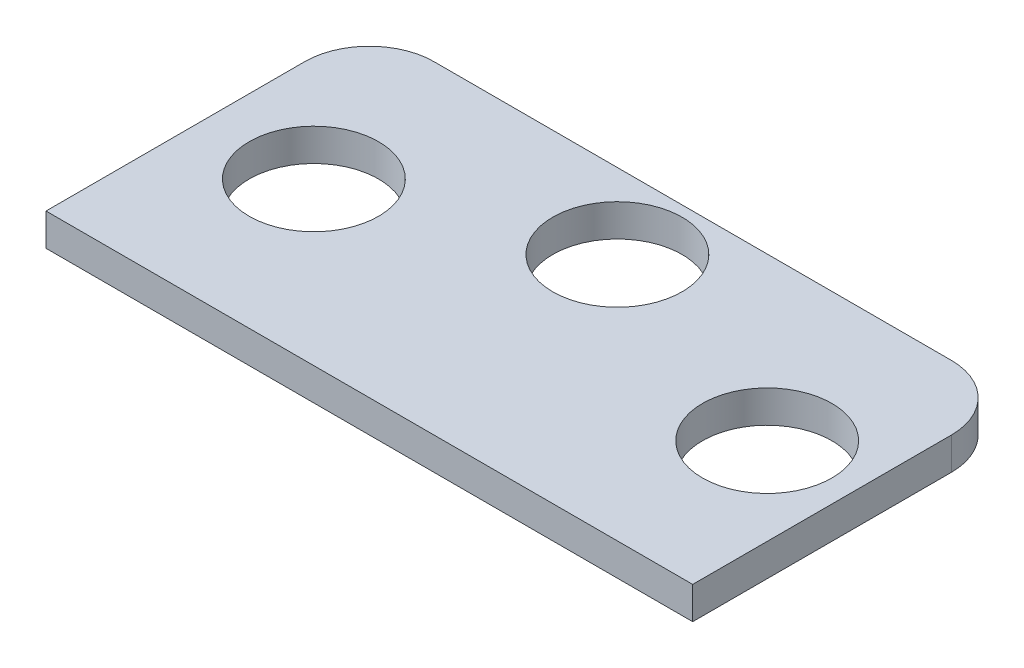
SolidWorks part; units mm, degrees
ref_plane "Front Plane" through (0, 0, 0) normal (0, 0, 1) x (1, 0, 0)
ref_plane "Top Plane" through (0, 0, 0) normal (0, 1, 0) x (1, 0, 0)
ref_plane "Right Plane" through (0, 0, 0) normal (1, 0, 0) x (0, 0, -1)
sketch "Sketch1" plane through (0, 0, 0) normal (0, 1, 0) x (1, 0, 0)
  line L1 (-80, 50) -> (80, 50)
  line L2 (-100, 30) -> (-100, -50)
  line L3 (-100, -50) -> (100, -50)
  line L4 (100, 30) -> (100, -50)
  line L5 (-100, 50) -> (100, -50) construction
  line L6 (-100, -50) -> (100, 50) construction
  circle A0 centre (0, 26.7157) radius 20
  circle A1 centre (73.0392, 0) radius 20
  circle A2 centre (-67.1569, 0) radius 20
  arc A3 (100, 30) -> (80, 50) centre (80, 30) ccw
  arc A4 (-80, 50) -> (-100, 30) centre (-80, 30) ccw
  point P0 (0, 0)
  point P18 (0, 0)
  dimension "D3" = 40
  dimension "D4" = 40
  dimension "D5" = 40
  dimension "D6" = 20
  dimension "D1" = 200
  dimension "D2" = 100
extrude "Boss-Extrude3" add sketch "Sketch1" along normal blind 10 contours L2 A4 L1 A3 L4 L3 | A2 | A0 | A1
